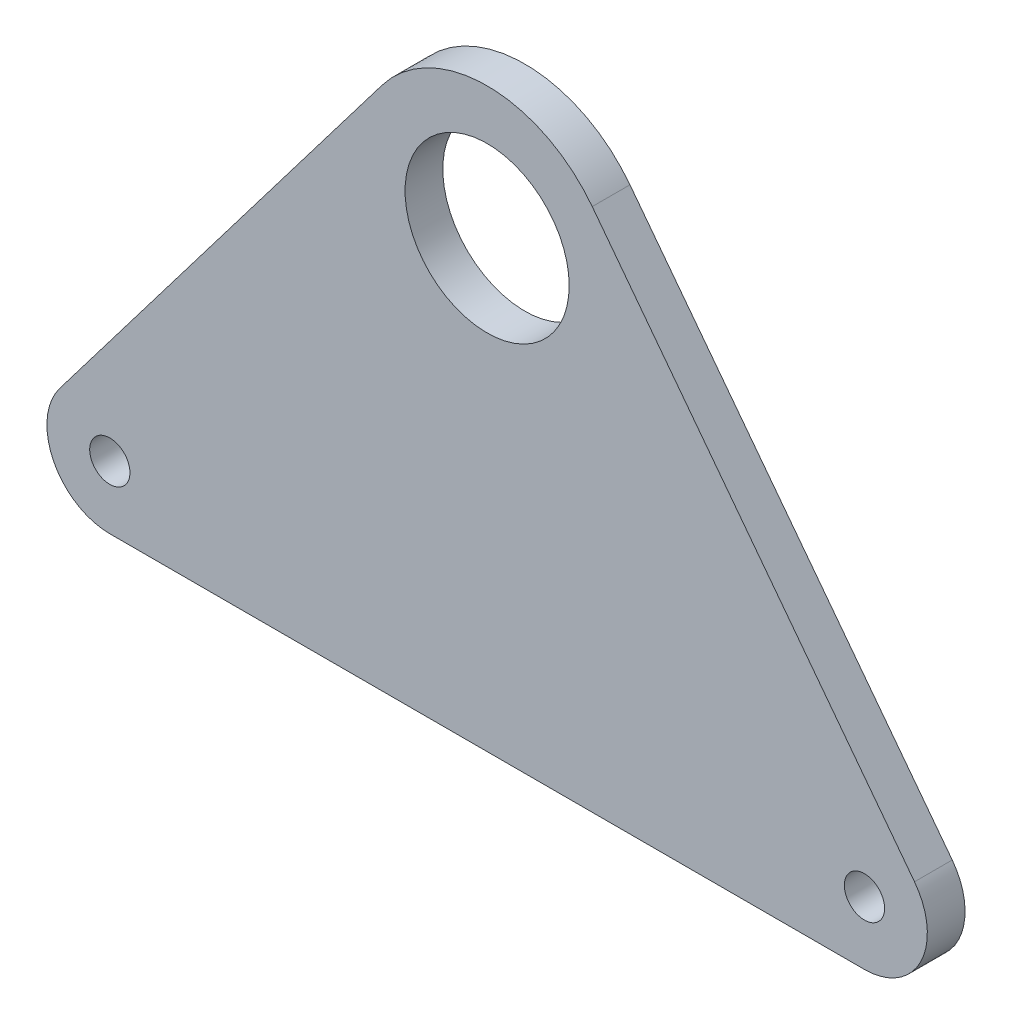
SolidWorks part; units mm, degrees
material "5052-O"
ref_plane "正面" through (0, 0, 0) normal (0, 0, 1) x (1, 0, 0)
ref_plane "平面" through (0, 0, 0) normal (0, 1, 0) x (1, 0, 0)
ref_plane "右側面" through (0, 0, 0) normal (1, 0, 0) x (0, 0, -1)
sketch "ｽｹｯﾁ1" plane through (0, 0, 0) normal (0, 0, 1) x (1, 0, 0)
  line L0 (0, 0) -> (0, -30.35) construction
  line L1 (30, -30.35) -> (-30, -30.35) construction
  line L2 (-8.3566, 6.3574) -> (-33.9793, -27.3226)
  line L3 (8.3566, 6.3574) -> (33.9793, -27.3226)
  line L4 (-30, -35.35) -> (30, -35.35)
  circle A0 centre (0, 0) radius 6.525
  circle A1 centre (-30, -30.35) radius 1.6
  circle A2 centre (30, -30.35) radius 1.6
  arc A3 (-33.9793, -27.3226) -> (-30, -35.35) centre (-30, -30.35) ccw
  arc A4 (8.3566, 6.3574) -> (-8.3566, 6.3574) centre (0, 0) ccw
  arc A5 (33.9793, -27.3226) -> (30, -35.35) centre (30, -30.35) cw
  dimension "D1" = 60
  dimension "D3" = 3.2
  dimension "D4" = 13.05
  dimension "D5" = 10.5
  dimension "D6" = 5
  dimension "D2" = 30.35
extrude "ﾎﾞｽ - 押し出し1" add sketch "ｽｹｯﾁ1" along normal blind 3
